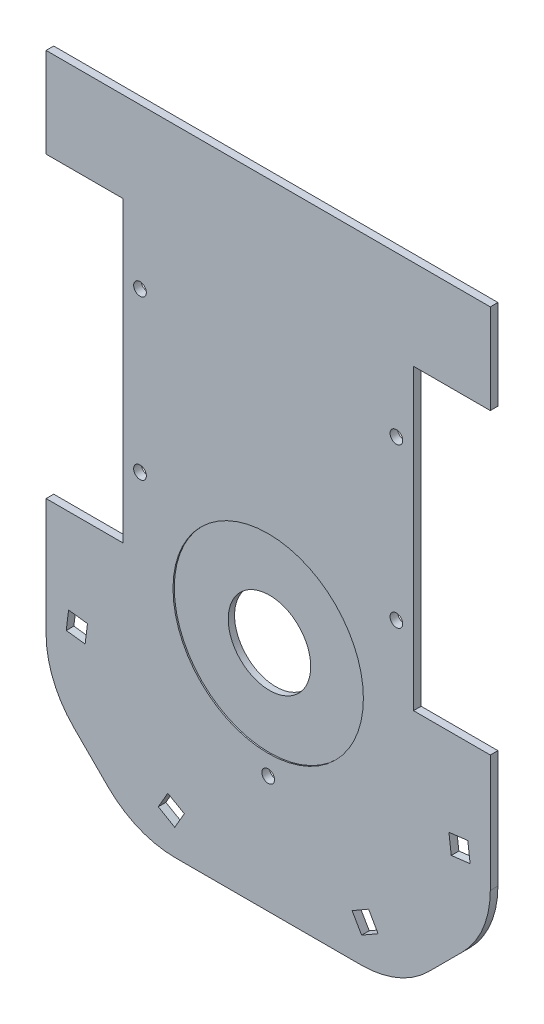
SolidWorks part; units mm, degrees
ref_plane "正面" through (0, 0, 0) normal (1, 0, 0) x (0, 1, 0)
ref_plane "平面" through (0, 0, 0) normal (0, 0, 1) x (0, 1, 0)
ref_plane "右側面" through (0, 0, 0) normal (0, 1, 0) x (-1, 0, 0)
sketch "ｽｹｯﾁ1" plane through (0, 0, 0) normal (0, 0, 1) x (0, 1, 0)
  line L0 (0, 0) -> (-115.3965, 0) construction
  line L1 (0, -35) -> (-100, -35)
  line L2 (0, -35) -> (0, 35)
  line L3 (0, 35) -> (-100, 35)
  line L4 (-100, -35) -> (-100, 35)
  line L5 (-54.6576, -17.9) -> (-20.6576, -17.9)
  line L6 (-54.6576, 22.9) -> (-20.6576, 22.9)
  line L7 (-54.6576, 22.9) -> (-54.6576, 17.9)
  line L8 (-54.6576, 17.9) -> (-20.6576, 17.9)
  line L9 (-20.6576, 22.9) -> (-20.6576, 17.9)
  line L10 (-20.6576, -22.9) -> (-20.6576, -17.9)
  line L11 (-54.6576, -22.9) -> (-20.6576, -22.9)
  line L12 (-54.6576, -22.9) -> (-54.6576, -17.9)
  line L13 (-37.6576, 17.9) -> (-37.6576, 22.9) construction
  line L14 (-100, 35) -> (0, -35) construction
  line L15 (-62.6576, 31.7098) -> (-12.6576, 31.7098) construction
  line L16 (-62.6576, 31.7098) -> (-62.6576, 22.9) construction
  line L17 (-62.6576, 22.9) -> (-12.6576, 22.9) construction
  line L18 (-12.6576, 31.7098) -> (-12.6576, 22.9) construction
  line L19 (-100, -35) -> (0, 35) construction
  circle A0 centre (-25.1476, 20.2) radius 1
  circle A1 centre (-50.1676, 20.2) radius 1
  circle A2 centre (-25.1476, -20.2) radius 1
  circle A3 centre (-50.1676, -20.2) radius 1
  circle A4 centre (-63.4417, 0) radius 6.5
  circle A5 centre (-63.4417, 0) radius 15
  circle A6 centre (-81.5344, 0) radius 1
  circle A7 centre (-50, 0) radius 0.6018 construction
  point P4 (0, 0)
  point P35 (-37.6576, 22.9)
  dimension "D6" = 2
  dimension "D7" = 4.49
  dimension "D8" = 2.7
  dimension "D9" = 13
  dimension "D10" = 30
  dimension "D11" = 2
  dimension "D1" = 100
  dimension "D2" = 70
  dimension "D3" = 5
  dimension "D4" = 34
  dimension "D5" = 45.8
  dimension "D12" = 50
  dimension "D13" = 50
sketch "ｽｹｯﾁ2" plane through (0, 0, 0) normal (0, 0, 1) x (0, 1, 0)
  line L0 (-54.6576, 22.9) -> (-20.6576, 22.9) construction
  line L1 (-61.1576, 22.9) -> (-14.1576, 22.9)
  line L2 (-61.1576, 22.9) -> (-61.1576, 35)
  line L3 (-61.1576, 35) -> (-14.1576, 35)
  line L4 (-14.1576, 22.9) -> (-14.1576, 35)
  line L5 (0, 35) -> (-100, 35) construction
  line L6 (-103.5266, 0) -> (14.7206, 0) construction
  line L8 (-61.1576, -35) -> (-14.1576, -35)
  line L9 (-14.1576, -22.9) -> (-14.1576, -35)
  line L10 (-61.1576, -22.9) -> (-14.1576, -22.9)
  line L11 (-61.1576, -22.9) -> (-61.1576, -35)
  point P8 (-37.6576, 22.9)
  dimension "D1" = 47
extrude "ﾎﾞｽ - 押し出し2" add sketch "ｽｹｯﾁ1" against normal blind 1.2 contours L12 L11 L10 L5 A3 A2 | L9 L6 L7 L8 A0 A1 | L2 L1 L4 L3 | A4 | A6
extrude "ｶｯﾄ - 押し出し1" cut sketch "ｽｹｯﾁ2" against normal through all
sketch "ｽｹｯﾁ4" plane through (0, 0, 0) normal (0, 0, 1) x (1, 0, 0)
  circle A0 centre (0, -63.4417) radius 15
  dimension "D1" = 30
extrude "ｶｯﾄ - 押し出し2" cut sketch "ｽｹｯﾁ4" against normal blind 0.2
sketch "ｽｹｯﾁ7" plane through (0, 0, 0) normal (0, 0, 1) x (1, 0, 0)
  line L0 (-35, -85.8579) -> (-20.8579, -100)
  line L2 (35, -100) -> (-35, -100) construction
  line L4 (-35, -85.8579) -> (-35, -100)
  line L5 (-35, -61.1576) -> (-35, -100) construction
  line L7 (-35, -100) -> (-20.8579, -100)
  line L8 (0, -100) -> (0, -92.891) construction
  line L9 (35, -85.8579) -> (35, -100)
  line L10 (35, -85.8579) -> (20.8579, -100)
  line L11 (35, -100) -> (20.8579, -100)
  dimension "D1" = 20
  dimension "D2" = 135
extrude "ｶｯﾄ - 押し出し4" cut sketch "ｽｹｯﾁ7" against normal through all
fillet "ﾌｨﾚｯﾄ3" radius 15 4 edges at (35, -85.8579, -0.6) (20.8579, -100, -0.6) (-20.8579, -100, -0.6) (-35, -85.8579, -0.6)
sketch "ｽｹｯﾁ11" plane through (0, 0, 0) normal (0, 0, 1) x (1, 0, 0)
  line L0 (-22.9, -14.1576) -> (22.9, -61.1576) construction
  line L1 (22.9, -14.1576) -> (-22.9, -61.1576) construction
  line L2 (0, -37.6576) -> (0, -127.6576) construction
  line L3 (-90, -127.6576) -> (90, -127.6576) construction
  line L4 (-90, -127.6576) -> (-90, 52.3424) construction
  line L5 (-90, 52.3424) -> (90, 52.3424) construction
  line L6 (90, -127.6576) -> (90, 52.3424) construction
  line L7 (-90, -127.6576) -> (90, 52.3424) construction
  line L8 (-90, 52.3424) -> (90, -127.6576) construction
  line L9 (-90, -127.6576) -> (90, -127.6576) construction
  line L10 (-90, -127.6576) -> (-90, -307.6576) construction
  line L11 (-90, -307.6576) -> (90, -307.6576) construction
  line L12 (90, -127.6576) -> (90, -307.6576) construction
  line L13 (-84, -121.6576) -> (-96, -121.6576) construction
  line L14 (-84, -121.6576) -> (-84, -133.6576) construction
  line L15 (-84, -133.6576) -> (-96, -133.6576) construction
  line L16 (-96, -121.6576) -> (-96, -133.6576) construction
  line L17 (-84, -121.6576) -> (-96, -133.6576) construction
  line L18 (-84, -133.6576) -> (-96, -121.6576) construction
  line L19 (-96, -133.6576) -> (-84, -133.6576) construction
  line L20 (-96, -133.6576) -> (-96, -173.6576) construction
  line L21 (-96, -173.6576) -> (-84, -173.6576) construction
  line L22 (-84, -133.6576) -> (-84, -173.6576) construction
  line L23 (30.3338, -77.759) -> (65.0021, -360.1095) construction
  line L24 (31.8226, -77.5762) -> (28.845, -77.9419)
  line L25 (31.8226, -77.5762) -> (31.457, -74.5986)
  line L26 (31.457, -74.5986) -> (28.4794, -74.9642)
  line L27 (28.845, -77.9419) -> (28.4794, -74.9642)
  line L28 (15.8202, -91.7848) -> (13.2221, -93.2848)
  line L29 (13.2221, -93.2848) -> (14.7221, -95.8829)
  line L30 (14.7221, -95.8829) -> (17.3202, -94.3829)
  line L31 (17.3202, -94.3829) -> (15.8202, -91.7848)
  line L32 (16.5702, -93.0838) -> (-143.0745, -185.2547) construction
  line L33 (14.6447, -100) -> (-14.6447, -100) construction
  line L34 (-84, -133.6576) -> (-84, -151.1481) construction
  line L35 (-96, -133.6576) -> (-96, -158.0763) construction
  line L36 (-31.457, -74.5986) -> (-28.4794, -74.9642)
  line L37 (-28.845, -77.9419) -> (-28.4794, -74.9642)
  line L38 (-31.8226, -77.5762) -> (-28.845, -77.9419)
  line L39 (-31.8226, -77.5762) -> (-31.457, -74.5986)
  line L40 (-14.7221, -95.8829) -> (-17.3202, -94.3829)
  line L41 (-13.2221, -93.2848) -> (-14.7221, -95.8829)
  line L42 (-15.8202, -91.7848) -> (-13.2221, -93.2848)
  line L43 (-17.3202, -94.3829) -> (-15.8202, -91.7848)
  circle A0 centre (0, -100) radius 0.0309 construction
  point P8 (0, -37.6576)
  dimension "D1" = 180
  dimension "D2" = 180
  dimension "D3" = 180
  dimension "D4" = 12
  dimension "D5" = 12
  dimension "D6" = 40
  dimension "D7" = 3
  dimension "D8" = 3
  dimension "D9" = 3
  dimension "D10" = 3
  dimension "D11" = 17.4904
  dimension "D12" = 24.4186
extrude "ｶｯﾄ - 押し出し6" cut sketch "ｽｹｯﾁ11" against normal through all
sketch "ｽｹｯﾁ12" [suppressed] plane through (0, 0, 0) normal (0, 0, 1) x (0, 1, 0)
  line L0 (-60.1576, 22.9) -> (-15.1576, -22.9) construction
  line L1 (-142.8983, 88.834) -> (36.4167, 104.5221)
  line L2 (-142.8983, 88.834) -> (-127.2103, -90.481)
  line L3 (-127.2103, -90.481) -> (52.1048, -74.793)
  line L4 (36.4167, 104.5221) -> (52.1048, -74.793)
  line L5 (-60.1576, 22.9) -> (-15.1576, 22.9) construction
  line L6 (-60.1576, 22.9) -> (-60.1576, -22.9) construction
  line L7 (-60.1576, -22.9) -> (-15.1576, -22.9) construction
  line L8 (-15.1576, 22.9) -> (-15.1576, -22.9) construction
  line L9 (-15.1576, 22.9) -> (-60.1576, -22.9) construction
  line L10 (-93.2848, -13.2221) -> (-95.8829, -14.7221)
  line L11 (-95.8829, -14.7221) -> (-94.3829, -17.3202)
  line L12 (-94.3829, -17.3202) -> (-91.7848, -15.8202)
  line L13 (-91.7848, -15.8202) -> (-93.2848, -13.2221)
  line L14 (-93.0838, -16.5702) -> (-174.2729, 124.0534)
  line L15 (-148.3525, 82.3339) -> (-150.1048, 82.193)
  line L16 (-322.8983, 73.0861) -> (-142.8983, 88.834)
  line L17 (-322.8983, 73.0861) -> (-307.2103, -106.229)
  line L18 (-307.2103, -106.229) -> (-127.2103, -90.481)
  line L19 (-142.8983, 88.834) -> (-127.2103, -90.481)
  line L20 (-148.3525, 82.3339) -> (-136.3982, 83.3798)
  line L21 (-148.3525, 82.3339) -> (-149.3984, 94.2883)
  line L22 (-149.3984, 94.2883) -> (-137.4441, 95.3341)
  line L23 (-136.3982, 83.3798) -> (-137.4441, 95.3341)
  line L24 (-148.3525, 82.3339) -> (-137.4441, 95.3341) construction
  line L25 (-149.3984, 94.2883) -> (-136.3982, 83.3798) construction
  line L26 (-149.3984, 94.2883) -> (-223.9852, 87.7628)
  line L27 (-149.3984, 94.2883) -> (-148.3485, 82.2883)
  line L28 (-148.3485, 82.2883) -> (-222.9353, 75.7628)
  line L29 (-223.9852, 87.7628) -> (-222.9353, 75.7628)
  dimension "D1" = 180
  dimension "D2" = 180
  dimension "D3" = 180
  dimension "D4" = 12
  dimension "D5" = 12
  dimension "D6" = 12
  dimension "D7" = 1.7522
sketch "ｽｹｯﾁ13" [suppressed] plane through (0, 0, 0) normal (0, 0, 1) x (1, 0, 0)
  line L0 (0, 0) -> (0, -105.5808) construction
  line L1 (-22.9, -14.1576) -> (22.9, -61.1576) construction
  line L2 (22.9, -14.1576) -> (-22.9, -61.1576) construction
  line L3 (63.6396, -101.2972) -> (190.9188, 25.982)
  line L4 (190.9188, 25.982) -> (63.6396, 153.2612)
  line L5 (63.6396, 153.2612) -> (-63.6396, 25.982)
  line L6 (-63.6396, 25.982) -> (63.6396, -101.2972)
  line L7 (-63.6396, 25.982) -> (63.6396, -101.2972)
  line L8 (-63.6396, -228.5764) -> (-190.9188, -101.2972)
  line L9 (-190.9188, -101.2972) -> (-63.6396, 25.982)
  line L10 (63.6396, -101.2972) -> (-63.6396, -228.5764)
  line L11 (-29.9682, -74.7814) -> (-53.6719, -267.8327)
  line L12 (-28.4794, -74.9642) -> (-31.457, -74.5986) construction
  line L13 (-63.6396, -216.5764) -> (-75.6396, -228.5764)
  line L14 (-75.6396, -228.5764) -> (-63.6396, -240.5764)
  line L15 (-63.6396, -240.5764) -> (-51.6396, -228.5764)
  line L16 (-51.6396, -228.5764) -> (-63.6396, -216.5764)
  line L17 (-63.6396, -216.5764) -> (-63.6396, -240.5764)
  line L18 (-75.6396, -228.5764) -> (-51.6396, -228.5764)
  line L19 (-51.6396, -228.5764) -> (-49.1567, -231.0593)
  line L20 (-51.6396, -228.5764) -> (-29.9682, -74.7814)
  circle A0 centre (0, -37.6576) radius 46.021 construction
  point P17 (0, -37.6576)
  point P28 (-63.6396, -228.5764)
  dimension "D1" = 180
  dimension "D2" = 12
  dimension "D3" = 3.5113
  dimension "D4" = 1.021
sketch "ｽｹｯﾁ14" plane through (0, 0, 0) normal (0, 0, 1) x (1, 0, 0)
  line L0 (-13.2221, -93.2848) -> (-14.7221, -95.8829)
  line L1 (-14.7221, -95.8829) -> (-17.3202, -94.3829)
  line L2 (-17.3202, -94.3829) -> (-15.8202, -91.7848)
  line L3 (-15.8202, -91.7848) -> (-13.2221, -93.2848)
  line L4 (-15.5471, -97.3118) -> (-12.3971, -91.8559)
  line L5 (-12.3971, -91.8559) -> (-19.4985, -87.7559)
  line L6 (-19.4985, -87.7559) -> (-22.6485, -93.2118)
  line L7 (-22.6485, -93.2118) -> (-15.5471, -97.3118)
  line L8 (-33.4838, -77.3723) -> (-27.1838, -78.1458)
  line L9 (-31.8226, -77.5762) -> (-28.845, -77.9419) construction
  line L10 (-33.4838, -77.3723) -> (-32.477, -69.1723)
  line L11 (-32.477, -69.1723) -> (-26.177, -69.9458)
  line L12 (-26.177, -69.9458) -> (-27.1838, -78.1458)
  line L15 (19.4985, -87.7559) -> (22.6485, -93.2118)
  line L16 (12.3971, -91.8559) -> (19.4985, -87.7559)
  line L17 (15.5471, -97.3118) -> (12.3971, -91.8559)
  line L18 (22.6485, -93.2118) -> (15.5471, -97.3118)
  line L19 (32.477, -69.1723) -> (26.177, -69.9458)
  line L20 (33.4838, -77.3723) -> (32.477, -69.1723)
  line L21 (33.4838, -77.3723) -> (27.1838, -78.1458)
  line L22 (26.177, -69.9458) -> (27.1838, -78.1458)
  point P10 (-13.9721, -94.5838)
  point P11 (-13.9721, -94.5838)
  point P18 (-30.3338, -77.759)
  point P19 (-30.3338, -77.759)
  dimension "D1" = 6.3
  dimension "D2" = 8.2
  dimension "D3" = 6.3
  dimension "D4" = 8.2
